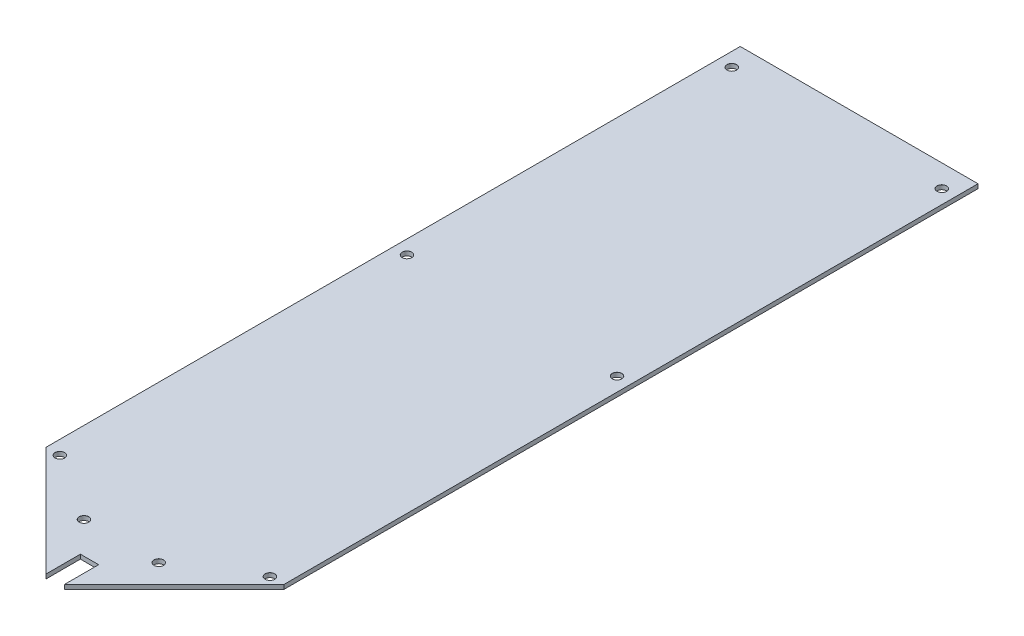
SolidWorks part; units mm, degrees
ref_plane "Front Plane" through (0, 0, 0) normal (0, 0, 1) x (1, 0, 0)
ref_plane "Top Plane" through (0, 0, 0) normal (0, 1, 0) x (1, 0, 0)
ref_plane "Right Plane" through (0, 0, 0) normal (1, 0, 0) x (0, 0, -1)
sketch "Sketch1" plane through (0, 0, 0) normal (0, 1, 0) x (1, 0, 0)
  line L0 (-82.7, 0) -> (82.7, 0) construction
  line L2 (6.35, 6.35) -> (82.7, 82.7)
  line L3 (82.7, 0) -> (82.7, 565.6605) construction
  line L4 (82.7, 82.7) -> (82.7, 565.6605)
  line L5 (-6.35, 30.2724) -> (6.35, 30.2724)
  line L8 (-6.35, 6.35) -> (-82.7, 82.7)
  line L9 (-82.7, 82.7) -> (-82.7, 565.6605)
  line L10 (-82.7, 565.6605) -> (82.7, 565.6605)
  line L11 (-6.35, 30.2724) -> (-6.35, 6.35)
  line L12 (6.35, 30.2724) -> (6.35, 6.35)
  point P4 (0, 0)
  dimension "D1" = 165.4
  dimension "D2" = 45
  dimension "D3" = 6.35
  dimension "D4" = 565.6605
  dimension "D5" = 30.2724
extrude "Boss-Extrude1" add sketch "Sketch1" against normal blind 3
sketch "Sketch2" plane through (0, 0, 0) normal (0, 1, 0) x (1, 0, 0)
  line L0 (0, 565.6605) -> (0, 30.2724) construction
  line L1 (-82.7, 324.1803) -> (82.7, 324.1803) construction
  line L2 (-82.7, 565.6605) -> (-82.7, 82.7) construction
  line L3 (82.7, 565.6605) -> (-82.7, 565.6605) construction
  line L4 (-6.35, 30.2724) -> (6.35, 30.2724) construction
  line L5 (-73.0567, 565.6605) -> (-73.0567, 73.0567) construction
  line L6 (-82.7, 82.7) -> (-6.35, 6.35) construction
  line L7 (82.7, 82.7) -> (82.7, 565.6605) construction
  line L8 (-82.7, 82.7) -> (-73.0567, 82.7) construction
  circle A0 centre (-73.0567, 550.1313) radius 3
  circle A1 centre (73.0567, 550.1313) radius 3
  circle A2 centre (-73.0567, 324.1803) radius 3
  circle A3 centre (-73.0567, 82.7) radius 3
  circle A4 centre (73.0567, 82.7) radius 3
  circle A5 centre (73.0567, 324.1803) radius 3
  circle A6 centre (-26.0149, 52.4348) radius 3
  circle A7 centre (26.0149, 52.4348) radius 3
  dimension "D1" = 6
  dimension "D2" = 9.6433
  dimension "D3" = 15.5292
  dimension "D4" = 513.2257
  dimension "D5" = 56.6851
hole_wizard "M6 Clearance Hole1" positions "3DSketch1" profile "Sketch3" hole size "M6" standard "ANSI Metric"
sketch3d "3DSketch1"
  point P0 (-73.0567, 0, -550.1313)
  point P3 (73.0567, 0, -550.1313)
  point P7 (-73.0567, 0, -324.1803)
  point P10 (73.0567, 0, -324.1803)
  point P13 (73.0567, 0, -82.7)
  point P16 (-73.0567, 0, -82.7)
  point P19 (-26.0149, 0, -52.4348)
  point P22 (26.0149, 0, -52.4348)
sketch "Sketch3" plane through (-73.0567, 0, -550.1313) normal (1, 0, 0) x (0, 0, 1)
  line L0 (0, 0) -> (0, 13.9828)
  line L1 (0, 13.9828) -> (3.3, 12)
  line L2 (3.3, 12) -> (3.3, 0.025)
  line L3 (3.3, 0.025) -> (3.325, 0)
  line L5 (3.325, 0) -> (0, 0)
  line L6 (-3.3, 0.025) -> (-3.325, 0) construction
  line L10 (0, 13.9828) -> (-3.3, 12) construction
  line L11 (0, -6.35) -> (0, 107.95) construction
  dimension "Hole Dia." = 6.6
  dimension "Hole Depth" = 12
  dimension "Near C'Sink Dia." = 6.65
  dimension "Near C'Sink Angle" = 90
  dimension "Drill Angle" = 118
